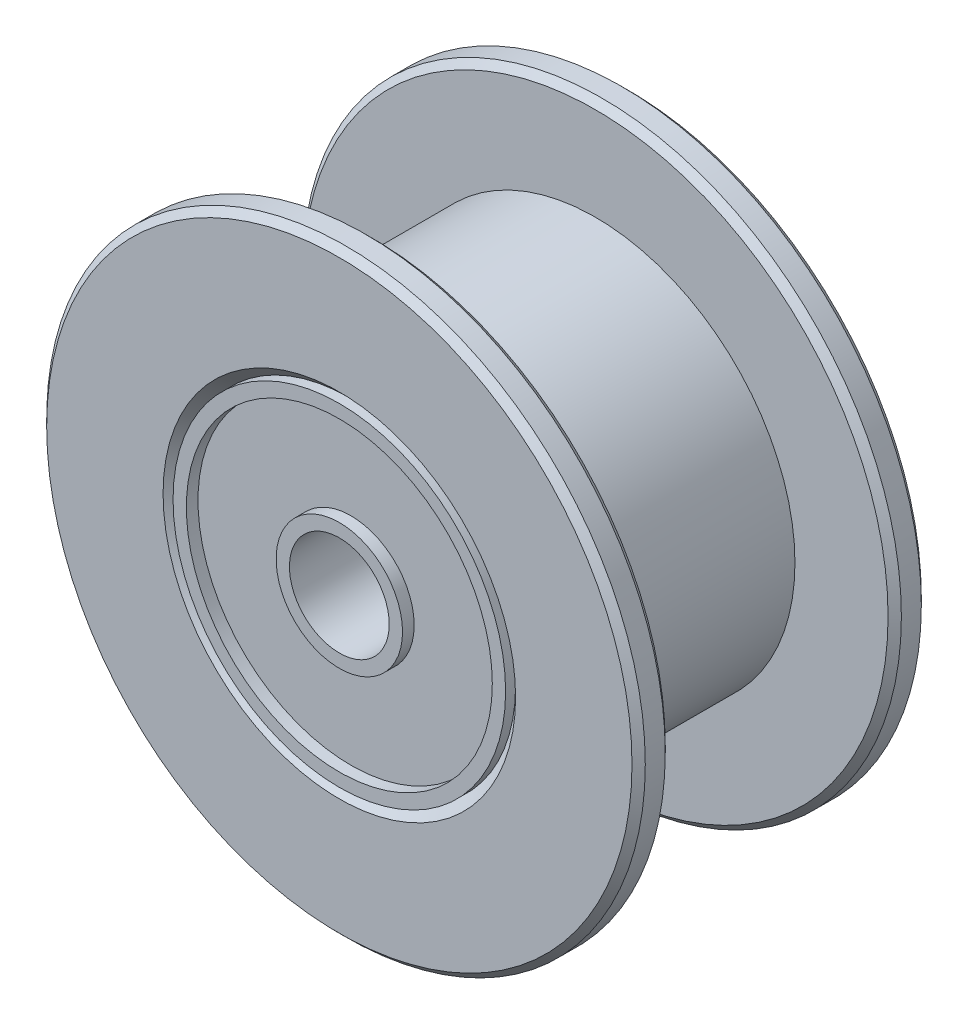
SolidWorks part; units mm, degrees
ref_plane "Спереди" through (0, 0, 0) normal (0, 0, 1) x (1, 0, 0)
ref_plane "Сверху" through (0, 0, 0) normal (0, 1, 0) x (1, 0, 0)
ref_plane "Справа" through (0, 0, 0) normal (1, 0, 0) x (0, 0, -1)
sketch "Эскиз1" plane through (0, 0, 0) normal (0, 1, 0) x (1, 0, 0)
  line L0 (4.6, 4.35) -> (4.6, 4)
  line L1 (4.6, 4) -> (1.9, 4)
  line L2 (1.9, 4) -> (1.9, 4.35)
  line L3 (1.9, 4.35) -> (1.5, 4.35)
  line L4 (1.5, 4.35) -> (1.5, -4.35)
  line L5 (1.5, -4.35) -> (1.9, -4.35)
  line L6 (1.9, -4.35) -> (1.9, -4)
  line L7 (1.9, -4) -> (4.6, -4)
  line L8 (4.6, -4) -> (4.6, -4.35)
  line L9 (4.6, -4.35) -> (5, -4.35)
  line L10 (5, -4.35) -> (5, -4.05)
  line L11 (5, -4.05) -> (5.3, -4.35)
  line L12 (5.3, -4.35) -> (8.8, -4.35)
  line L13 (8.8, -4.35) -> (9, -4.15)
  line L14 (9, -4.15) -> (9, -3.55)
  line L15 (9, -3.55) -> (8.8, -3.35)
  line L16 (8.8, -3.35) -> (6, -3.35)
  line L17 (6, -3.35) -> (6, 3.35)
  line L18 (6, 3.35) -> (8.8, 3.35)
  line L19 (8.8, 3.35) -> (9, 3.55)
  line L20 (9, 3.55) -> (9, 4.15)
  line L21 (9, 4.15) -> (8.8, 4.35)
  line L22 (8.8, 4.35) -> (5.3, 4.35)
  line L23 (5.3, 4.35) -> (5, 4.05)
  line L24 (5, 4.05) -> (5, 4.35)
  line L25 (5, 4.35) -> (4.6, 4.35)
  line L26 (0, 4.35) -> (0, -4.35) construction
revolve "Повернуть1" add sketch "Эскиз1" angle 360 about L26
